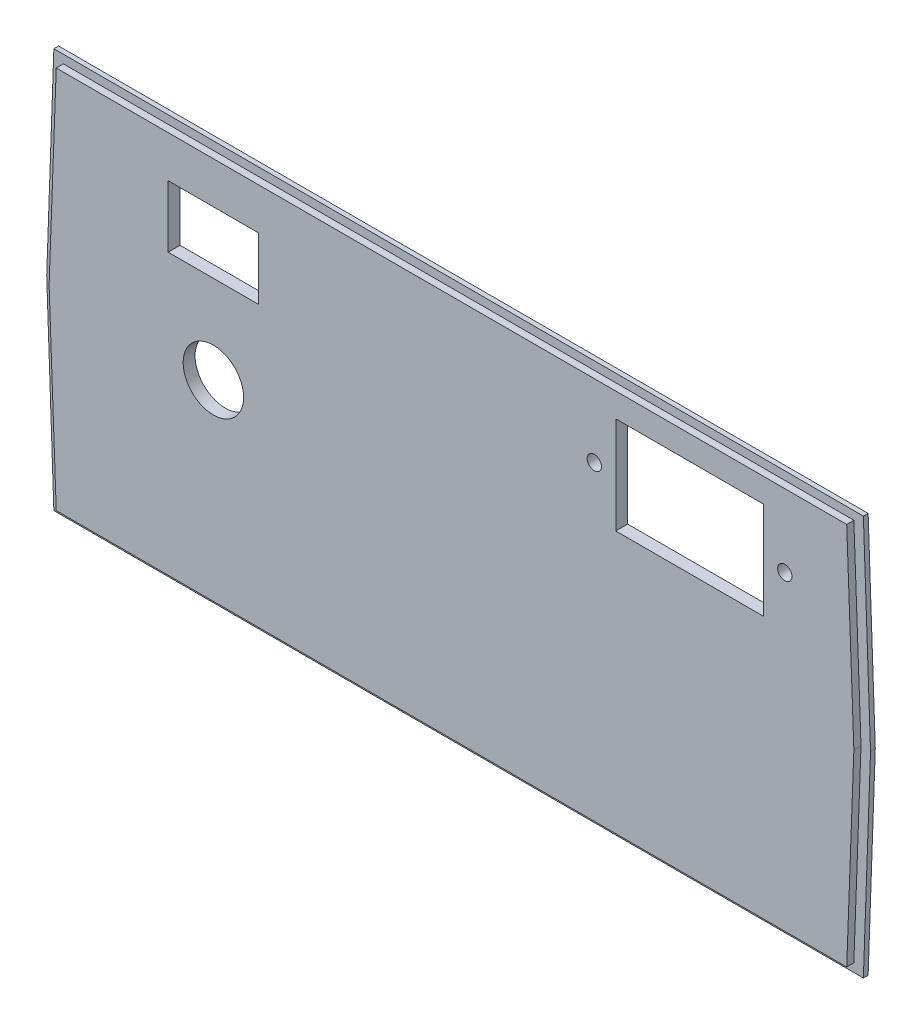
SolidWorks part; units mm, degrees
ref_plane "Front Plane" through (0, 0, 0) normal (0, 0, 1) x (1, 0, 0)
ref_plane "Top Plane" through (0, 0, 0) normal (0, 1, 0) x (1, 0, 0)
ref_plane "Right Plane" through (0, 0, 0) normal (1, 0, 0) x (0, 0, -1)
sketch "Sketch1" plane through (0, 0, 0) normal (0, 0, 1) x (1, 0, 0)
  line L1 (-85, 42) -> (85, 42)
  line L3 (-85, -42) -> (85, -42)
  line L5 (-85, 42) -> (85, -42) construction
  line L6 (-85, -42) -> (85, 42) construction
  line L7 (-86.5, 0) -> (-85, -42)
  line L8 (-85, 42) -> (-86.5, 0)
  line L9 (85, -42) -> (86.5, 0)
  line L10 (85, 42) -> (86.5, 0)
  point P0 (0, 0)
  dimension "D1" = 170
  dimension "D2" = 84
  dimension "D3" = 173
extrude "Boss-Extrude1" add sketch "Sketch1" along normal blind 1
sketch "Sketch2" plane through (0, 0, 1) normal (0, 0, 1) x (1, 0, 0)
  line L0 (-84.5, 0) -> (84.5, 0) construction
  line L1 (-83, 40.25) -> (83, 40.25)
  line L3 (-83, -40.25) -> (83, -40.25)
  line L5 (-83, 40.25) -> (83, -40.25) construction
  line L6 (-83, -40.25) -> (83, 40.25) construction
  line L7 (-83, -40.25) -> (-84.5, 0)
  line L8 (-84.5, 0) -> (-83, 40.25)
  line L9 (83, -40.25) -> (84.5, 0)
  line L10 (84.5, 0) -> (83, 40.25)
  point P0 (0, 0)
  dimension "D1" = 166
  dimension "D2" = 80.5
  dimension "D3" = 169
extrude "Boss-Extrude2" add sketch "Sketch2" along normal blind 1.5
sketch "Sketch3" plane through (0, 0, 0) normal (0, 0, -1) x (-1, 0, 0)
  line L0 (-85, 42) -> (85, 42) construction
  line L2 (-65.5, 35.2) -> (-34.5, 35.2)
  line L3 (-65.5, 35.2) -> (-65.5, 14.8)
  line L4 (-65.5, 14.8) -> (-34.5, 14.8)
  line L8 (-34.5, 35.2) -> (-34.5, 14.8)
  line L9 (-65.5, 35.2) -> (-34.5, 14.8) construction
  line L10 (-65.5, 14.8) -> (-34.5, 35.2) construction
  line L14 (40.5, 31.5) -> (59.5, 31.5)
  line L15 (40.5, 31.5) -> (40.5, 18.5)
  line L16 (40.5, 18.5) -> (59.5, 18.5)
  line L17 (59.5, 31.5) -> (59.5, 18.5)
  line L18 (40.5, 31.5) -> (59.5, 18.5) construction
  line L19 (40.5, 18.5) -> (59.5, 31.5) construction
  circle A6 centre (-70, 25) radius 1.5
  circle A7 centre (-30, 25) radius 1.5
  circle A8 centre (50, 0) radius 6.35
  point P26 (-50, 25)
  point P40 (50, 25)
  dimension "D6" = 17
  dimension "D7" = 20
  dimension "D8" = 35
  dimension "D9" = 15
  dimension "D11" = 135
  dimension "D13" = 3
  dimension "D15" = 12.7
  dimension "D5" = 3
  dimension "D2" = 35
  dimension "D3" = 25
  dimension "D4" = 17
  dimension "D10" = 20
  dimension "D12" = 31
  dimension "D14" = 20.4
  dimension "D16" = 55
  dimension "D17" = 13
  dimension "D18" = 19
  dimension "D19" = 135
  dimension "D20" = 42
extrude "Cut-Extrude1" cut sketch "Sketch3" against normal up to next
